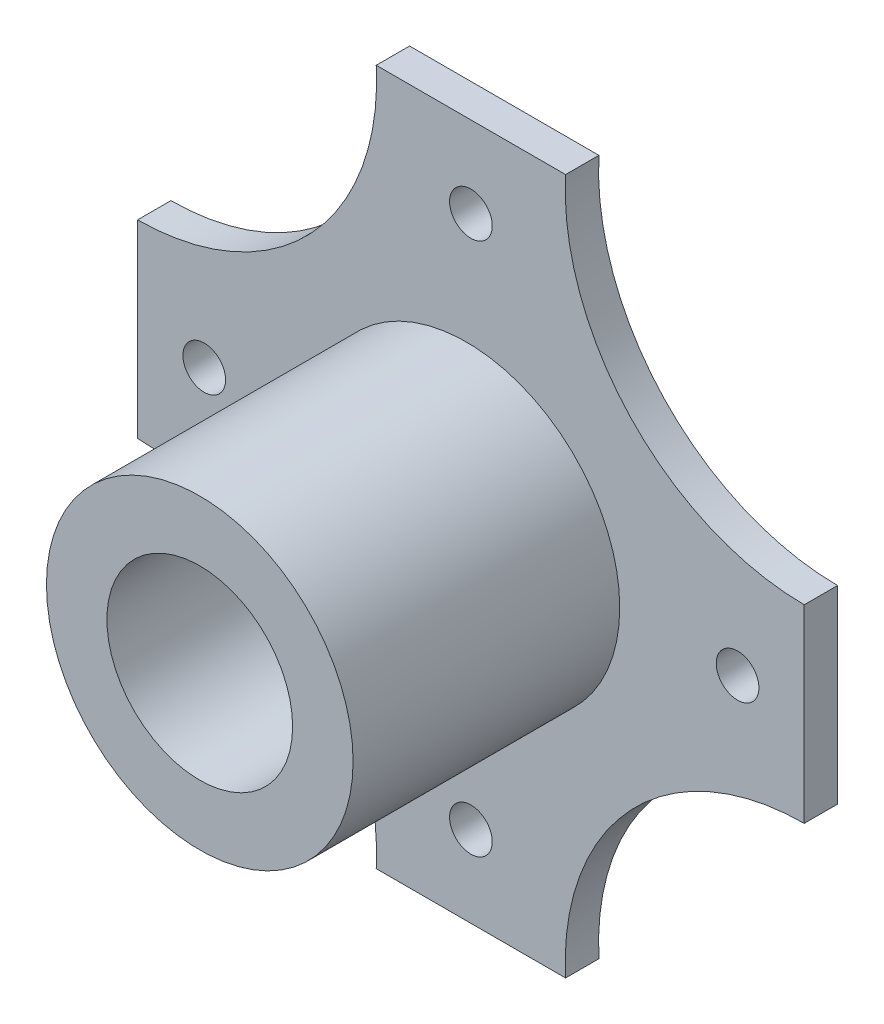
SolidWorks part; units mm, degrees
material "PET"
ref_plane "Front Plane" through (0, 0, 0) normal (0, 0, 1) x (1, 0, 0)
ref_plane "Top Plane" through (0, 0, 0) normal (0, 1, 0) x (1, 0, 0)
ref_plane "Right Plane" through (0, 0, 0) normal (1, 0, 0) x (0, 0, -1)
sketch "Sketch1" plane through (0, 0, 0) normal (0, 0, 1) x (1, 0, 0)
  line L0 (0.0923, 22.8598) -> (0.0923, 40.8942)
  line L8 (40.8595, -1.2618) -> (22.8251, -1.2618)
  line L9 (63.5923, 40.8942) -> (63.5923, 22.8598)
  line L10 (22.8251, 65.0158) -> (40.8595, 65.0158)
  line L11 (0.0923, 31.877) -> (63.5923, 31.877) construction
  line L12 (31.8423, 65.0158) -> (31.8423, -1.2618) construction
  circle A0 centre (6.4423, 31.877) radius 2.032
  circle A1 centre (31.8423, 57.277) radius 2.032
  circle A2 centre (57.2423, 31.877) radius 2.032
  circle A3 centre (31.8423, 6.477) radius 2.032
  arc A4 (22.8251, -1.2618) -> (0.0923, 22.8598) centre (0, 0) ccw
  arc A5 (40.8595, -1.2618) -> (63.5923, 22.8598) centre (63.6847, 0) cw
  arc A6 (22.8251, 65.0158) -> (0.0923, 40.8942) centre (0, 63.754) cw
  arc A7 (63.5923, 40.8942) -> (40.8595, 65.0158) centre (63.6847, 63.754) cw
  circle A8 centre (31.8423, 31.877) radius 25.4 construction
  point P3 (0, 0)
  point P6 (0, 0)
  point P7 (0, 0)
  point P8 (63.5, 40.894)
  point P9 (0, 0)
  point P10 (31.8423, 31.877)
  point P11 (41.0994, 68.3137)
  point P12 (0, 0)
  point P33 (-0.1437, 40.8945)
  point P36 (-2.3844, 41.0187)
  point P37 (-1.1568, 40.9233)
  point P38 (22.8251, 65.0158)
  point P39 (0, 0)
  point P40 (0, 0)
  point P41 (0, 0)
  dimension "D7" = 4.064
  dimension "D8" = 22.86
  dimension "D1" = 50.8
  dimension "D2" = 63.754
  dimension "D3" = 31.75
  dimension "D4" = 6.35
  dimension "D5" = 18.0344
  dimension "D6" = 6.35
extrude "Boss-Extrude1" add sketch "Sketch1" along normal blind 3.175
sketch "Sketch2" plane through (0, 0, 3.175) normal (0, 0, 1) x (1, 0, 0)
  line L0 (31.8423, 65.0158) -> (31.8423, -1.2618) construction
  line L3 (40.8595, 65.0158) -> (22.8251, 65.0158) construction
  line L6 (22.8251, -1.2618) -> (40.8595, -1.2618) construction
  line L7 (0.0923, 31.877) -> (63.5923, 31.877) construction
  line L8 (0.0923, 40.8942) -> (0.0923, 22.8598) construction
  line L9 (63.5923, 22.8598) -> (63.5923, 40.8942) construction
  circle A0 centre (31.4152, 31.877) radius 5.715
  dimension "D1" = 11.43
extrude "Cut-Extrude1" cut sketch "Sketch2" against normal blind 3.175
sketch "Sketch3" plane through (0, 0, 3.175) normal (0, 0, 1) x (1, 0, 0)
  circle A2 centre (31.4152, 31.877) radius 14.605
  circle A3 centre (31.4152, 31.877) radius 5.715 construction
  circle A4 centre (31.4152, 31.877) radius 5.715
  dimension "D1" = 29.21
extrude "Boss-Extrude2" add sketch "Sketch3" along normal blind 25.4
sketch "Sketch6" plane through (0, 0, 28.575) normal (0, 0, 1) x (1, 0, 0)
  circle A0 centre (31.4152, 31.877) radius 8.8455
extrude "Cut-Extrude3" cut sketch "Sketch6" against normal offset from surface (22.225 mm away) 6.35 up to face at (37.1302, 31.877, 0)
sketch "Sketch7" plane through (0, 0, 0) normal (0, 0, -1) x (-1, 0, 0)
  line L1 (-23.0565, 31.877) -> (-27.2358, 39.1158)
  line L2 (-27.2358, 39.1158) -> (-35.5945, 39.1158)
  line L3 (-35.5945, 39.1158) -> (-39.7738, 31.877)
  line L4 (-39.7738, 31.877) -> (-35.5945, 24.6382)
  line L5 (-35.5945, 24.6382) -> (-27.2358, 24.6382)
  line L6 (-27.2358, 24.6382) -> (-23.0565, 31.877)
  line L7 (-22.8251, -1.2618) -> (-40.8595, -1.2618) construction
  circle A0 centre (-31.4152, 31.877) radius 7.2388 construction
  dimension "D1" = 25.9
extrude "Cut-Extrude5" cut sketch "Sketch7" against normal offset from surface (3.175 mm away) 3.175 up to face at (37.1302, 31.877, 0)
